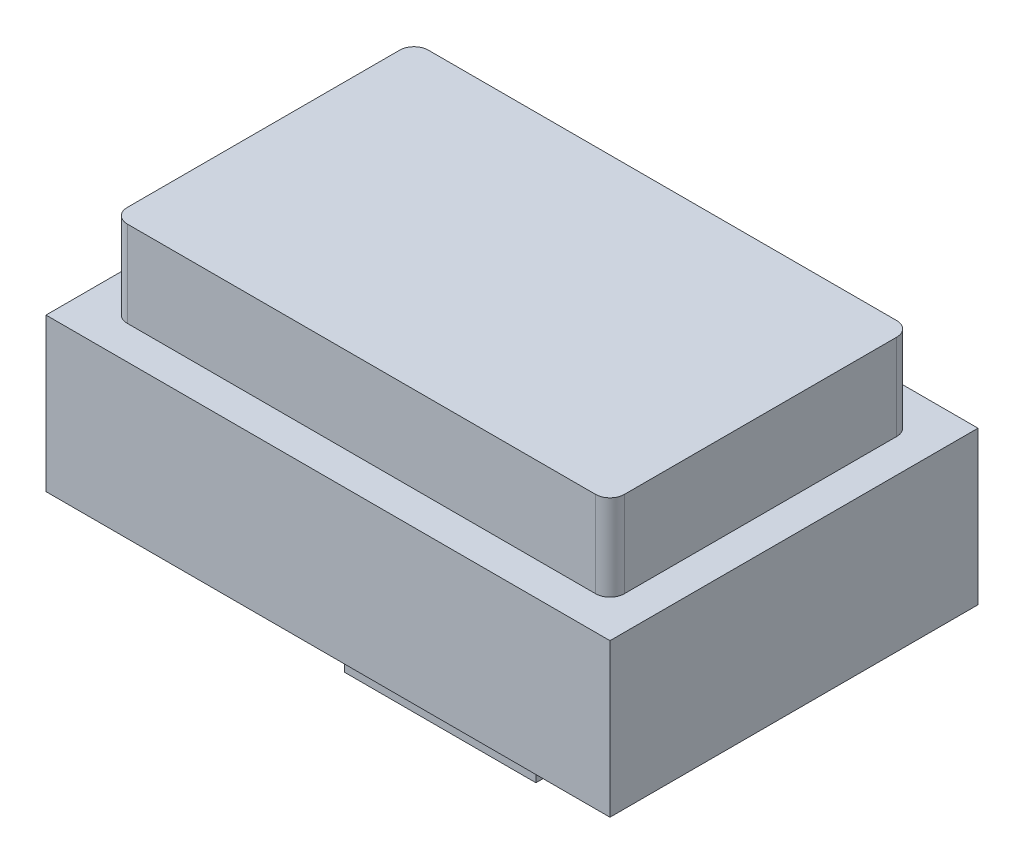
SolidWorks part; units mm, degrees
ref_plane "Front Plane" through (0, 0, 0) normal (0, 0, 1) x (1, 0, 0)
ref_plane "Top Plane" through (0, 0, 0) normal (0, 1, 0) x (1, 0, 0)
ref_plane "Right Plane" through (0, 0, 0) normal (1, 0, 0) x (0, 0, -1)
sketch "body-s" plane through (0, 0, 0) normal (0, 1, 0) x (1, 0, 0)
  line L1 (-5.2, 3.15) -> (5.2, 3.15)
  line L2 (-5.2, 3.15) -> (-5.2, -3.15)
  line L3 (-5.2, -3.15) -> (5.2, -3.15)
  line L4 (5.2, 3.15) -> (5.2, -3.15)
  line L5 (-5.2, 3.15) -> (5.2, -3.15) construction
  line L6 (-5.2, -3.15) -> (5.2, 3.15) construction
  point P0 (0, 0)
  dimension "D1" = 10.4
  dimension "D2" = 6.3
extrude "body" add sketch "body-s" along normal blind 1.8
fillet "edge-fillet" radius 0.3 4 edges at (-5.2, 0.9, 3.15) (5.2, 0.9, 3.15) (5.2, 0.9, -3.15) (-5.2, 0.9, -3.15)
sketch "base-s" plane through (0, 0, 0) normal (0, -1, 0) x (1, 0, 0)
  line L0 (-5.2, -2.85) -> (-5.2, 2.85) construction
  line L1 (-5.9, 3.85) -> (5.9, 3.85)
  line L2 (-5.9, 3.85) -> (-5.9, -3.85)
  line L3 (-5.9, -3.85) -> (5.9, -3.85)
  line L4 (5.9, 3.85) -> (5.9, -3.85)
  line L5 (-5.9, 3.85) -> (5.9, -3.85) construction
  line L6 (-5.9, -3.85) -> (5.9, 3.85) construction
  line L7 (-4.9, 3.15) -> (4.9, 3.15) construction
  point P0 (0, 0)
  dimension "D1" = 0.7
  dimension "D2" = 0.7
extrude "base" add sketch "base-s" along normal blind 3.2
sketch "peg-s" plane through (0, -3.2, 0) normal (0, -1, 0) x (1, 0, 0)
  line L1 (-2, 1.5) -> (2, 1.5)
  line L2 (-2, 1.5) -> (-2, -1.5)
  line L3 (-2, -1.5) -> (2, -1.5)
  line L4 (2, 1.5) -> (2, -1.5)
  line L5 (-2, 1.5) -> (2, -1.5) construction
  line L6 (-2, -1.5) -> (2, 1.5) construction
  point P0 (0, 0)
  dimension "D1" = 3
  dimension "D2" = 4
extrude "peg" add sketch "peg-s" along normal blind 2.5
